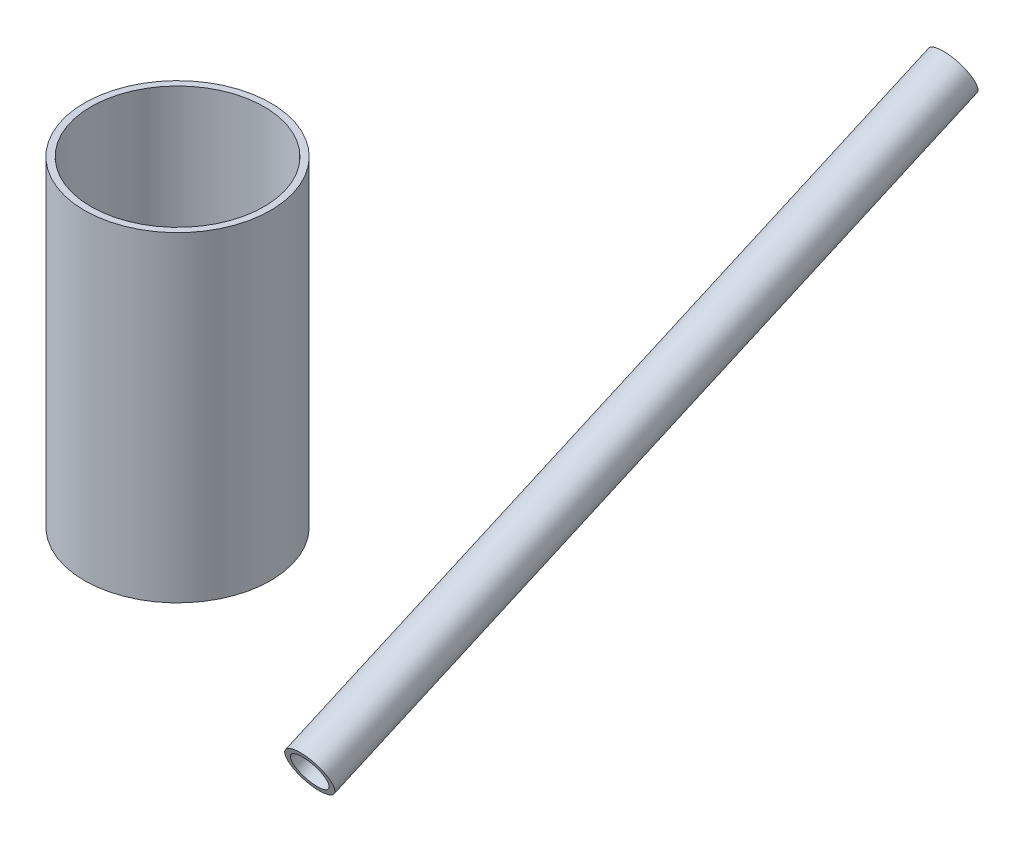
SolidWorks part; units mm, degrees
ref_plane "Front Plane" through (0, 0, 0) normal (0, 0, 1) x (1, 0, 0)
ref_plane "Top Plane" through (0, 0, 0) normal (0, 1, 0) x (1, 0, 0)
ref_plane "Right Plane" through (0, 0, 0) normal (1, 0, 0) x (0, 0, -1)
sketch "Sketch1" plane through (0, 0, 0) normal (0, 0, 1) x (1, 0, 0)
  line L0 (-56.5795, -3.74) -> (-56.5795, 39.9892)
ref_plane "Plane1" through (-56.5795, -3.74, 0) normal (0, 1, 0) x (-1, 0, 0)
other "Weld tubing 1.00 X 0.035<AS MACHINED>(1)"
ref_plane "Plane2" through (-56.5795, -3.74, 0) normal (0, 1, 0) x (-1, 0, 0)
sketch "Sketch16" plane through (-56.5795, -3.74, 0) normal (0, 1, 0) x (-1, 0, 0)
  circle A0 centre (0, 0) radius 12.7
  circle A1 centre (0, 0) radius 11.811
  point P5 (0, 0)
  dimension "D1" = 25.4
  dimension "D2" = 0.889
sketch "Sketch17" plane through (0, 0, 0) normal (1, 0, 0) x (0, 0, -1)
  line L0 (-38.5448, 14.9081) -> (49.1658, 53.8906)
other "Weld tubing 0.250 X 0.028(1)"
ref_plane "Plane3" through (0, 14.9081, 38.5448) normal (0, 0.4061, -0.9138) x (0, 0.9138, 0.4061)
sketch "Sketch114" plane through (0, 14.9081, 38.5448) normal (0, 0.4061, -0.9138) x (0, 0.9138, 0.4061)
  circle A0 centre (0, 0) radius 3.175
  circle A1 centre (0, 0) radius 2.4638
  point P5 (0, 0)
  dimension "D1" = 6.35
  dimension "D2" = 0.7112
